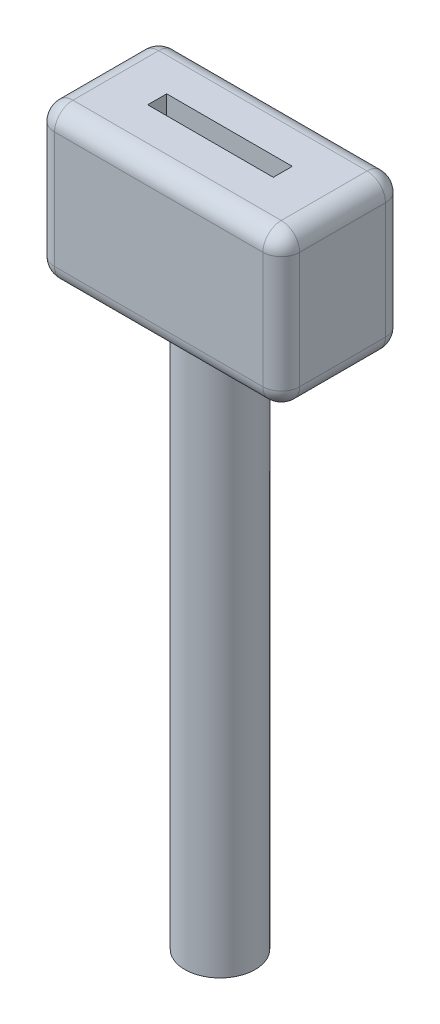
SolidWorks part; units mm, degrees
ref_plane "前视基准面" through (0, 0, 0) normal (0, 0, 1) x (1, 0, 0)
ref_plane "上视基准面" through (0, 0, 0) normal (0, 1, 0) x (1, 0, 0)
ref_plane "右视基准面" through (0, 0, 0) normal (1, 0, 0) x (0, 0, -1)
other "Configuration Table"
sketch "草图1" plane through (0, 0, 0) normal (0, 1, 0) x (1, 0, 0)
  circle A0 centre (0, 0) radius 5.75
  dimension "D1" = 11.5
extrude "凸台-拉伸1" add sketch "草图1" along normal blind 90
sketch "草图2" plane through (0, 90, 0) normal (0, 1, 0) x (1, 0, 0)
  line L1 (-20, -10) -> (20, -10)
  line L2 (-20, -10) -> (-20, 10)
  line L3 (-20, 10) -> (20, 10)
  line L4 (20, -10) -> (20, 10)
  line L5 (-20, -10) -> (20, 10) construction
  line L6 (-20, 10) -> (20, -10) construction
  point P0 (0, 0)
  dimension "D1" = 40
  dimension "D2" = 20
extrude "凸台-拉伸2" add sketch "草图2" along normal blind 25
sketch "草图3" plane through (0, 115, 0) normal (0, 1, 0) x (1, 0, 0)
  line L1 (-10.25, -1.55) -> (10.25, -1.55)
  line L2 (-10.25, -1.55) -> (-10.25, 1.55)
  line L3 (-10.25, 1.55) -> (10.25, 1.55)
  line L4 (10.25, -1.55) -> (10.25, 1.55)
  line L5 (-10.25, -1.55) -> (10.25, 1.55) construction
  line L6 (-10.25, 1.55) -> (10.25, -1.55) construction
  point P0 (0, 0)
  dimension "D1" = 20.5
  dimension "D2" = 3.1
extrude "切除-拉伸1" cut sketch "草图3" against normal blind 20
fillet "圆角1" radius 3 12 edges at (20, 102.5, -10) (0, 115, -10) (-20, 102.5, -10) (0, 90, -10) (-20, 102.5, 10) (0, 115, 10) (20, 102.5, 10) (0, 90, 10) (-20, 115, 0) (-20, 90, 0) (20, 115, 0) (20, 90, 0)
